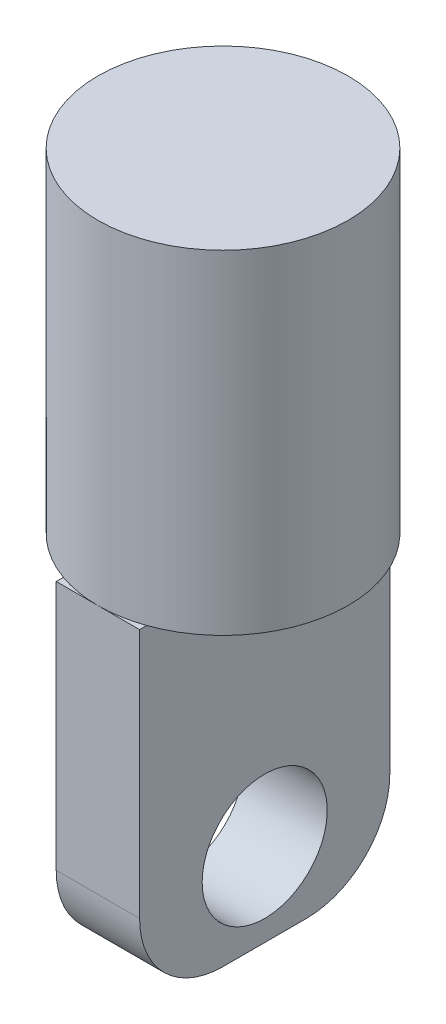
SolidWorks part; units mm, degrees
ref_plane "Front Plane" through (0, 0, 0) normal (0, 0, 1) x (1, 0, 0)
ref_plane "Top Plane" through (0, 0, 0) normal (0, 1, 0) x (1, 0, 0)
ref_plane "Right Plane" through (0, 0, 0) normal (1, 0, 0) x (0, 0, -1)
sketch "Sketch1" plane through (0, 0, 0) normal (0, 1, 0) x (1, 0, 0)
  circle A0 centre (0, 0) radius 15
  dimension "D1" = 30
extrude "Boss-Extrude1" add sketch "Sketch1" along normal blind 40
sketch "Sketch2" plane through (0, 0, 0) normal (0, -1, 0) x (1, 0, 0)
  line L1 (-5, 15) -> (5, 15)
  line L2 (-5, 15) -> (-5, -15)
  line L3 (-5, -15) -> (5, -15)
  line L4 (5, 15) -> (5, -15)
  line L5 (-5, 15) -> (5, -15) construction
  line L6 (-5, -15) -> (5, 15) construction
  point P0 (0, 0)
  dimension "D1" = 30
  dimension "D2" = 10
extrude "Boss-Extrude2" add sketch "Sketch2" along normal blind 40
sketch "Sketch3" plane through (-5, 0, 0) normal (-1, 0, 0) x (0, 0, 1)
  line L0 (-15, 0) -> (15, -40) construction
  line L1 (-15, -40) -> (15, 0) construction
  line L2 (0, -20) -> (0, -40) construction
  line L3 (15, -40) -> (-15, -40) construction
  circle A0 centre (0, -30) radius 7.5
  dimension "D1" = 15
extrude "Cut-Extrude1" cut sketch "Sketch3" against normal blind 40
fillet "Fillet2" radius 10 2 edges at (0, -40, -15) (0, -40, 15)
